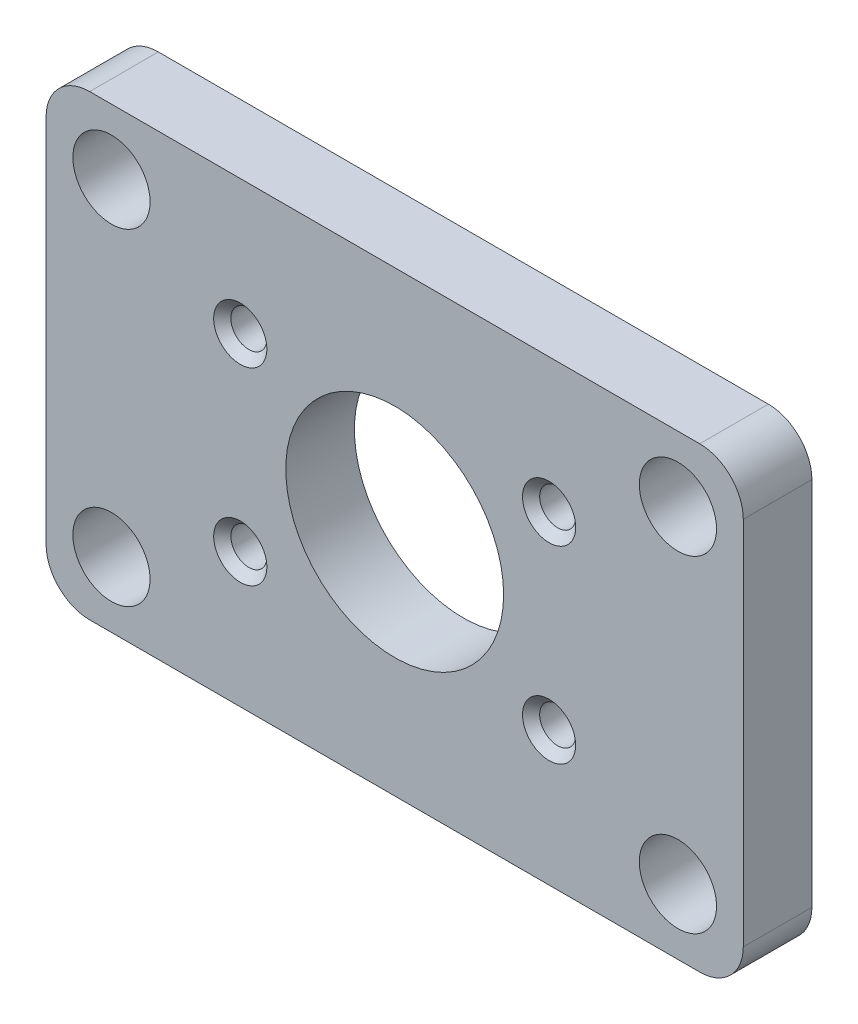
SolidWorks part; units mm, degrees
ref_plane "Front Plane" through (0, 0, 0) normal (0, 0, 1) x (1, 0, 0)
ref_plane "Top Plane" through (0, 0, 0) normal (0, 1, 0) x (1, 0, 0)
ref_plane "Right Plane" through (0, 0, 0) normal (1, 0, 0) x (0, 0, -1)
sketch "Sketch1" plane through (0, 0, 0) normal (0, 0, 1) x (1, 0, 0)
  line L0 (0, 0) -> (-20.32, 0) construction
  line L1 (20.32, -13.335) -> (-20.32, -13.335)
  line L2 (20.32, -13.335) -> (20.32, 13.335)
  line L3 (20.32, 13.335) -> (-20.32, 13.335)
  line L4 (-20.32, -13.335) -> (-20.32, 13.335)
  line L5 (20.32, -13.335) -> (-20.32, 13.335) construction
  line L6 (20.32, 13.335) -> (-20.32, -13.335) construction
  line L7 (0, 0) -> (0, 13.335) construction
  line L8 (-9.0005, 5.5004) -> (9.0005, 5.5004) construction
  line L9 (9.0005, 5.5004) -> (9.0005, -5.5004) construction
  circle A0 centre (-16.51, 9.525) radius 2.25
  circle A1 centre (16.51, 9.525) radius 2.25
  circle A2 centre (16.51, -9.525) radius 2.25
  circle A3 centre (-16.51, -9.525) radius 2.25
  circle A4 centre (-9.0005, 5.5004) radius 1.05
  circle A5 centre (9.0005, -5.5004) radius 1.05
  circle A6 centre (0, 0) radius 6.35
  circle A7 centre (-9.0005, -5.5004) radius 1.05
  circle A8 centre (9.0005, 5.5004) radius 1.05
  point P0 (0, 0)
  point P22 (0, 5.5004)
  point P24 (9.0005, 0)
  dimension "D3" = 4.5
  dimension "D6" = 2.1
  dimension "D9" = 12.7
  dimension "D1" = 26.67
  dimension "D2" = 40.64
  dimension "D4" = 19.05
  dimension "D5" = 33.02
  dimension "D7" = 18.001
  dimension "D8" = 11.0007
extrude "Boss-Extrude1" add sketch "Sketch1" along normal blind 4
fillet "Fillet1" radius 2.54 4 edges at (20.32, 13.335, 2) (20.32, -13.335, 2) (-20.32, -13.335, 2) (-20.32, 13.335, 2)
chamfer "Chamfer1" distance 0.5 angle 45 4 edges at (10.0505, -5.5004, 4) (7.9505, 5.5004, 4) (-10.0505, -5.5004, 4) (-7.9505, 5.5004, 4)
